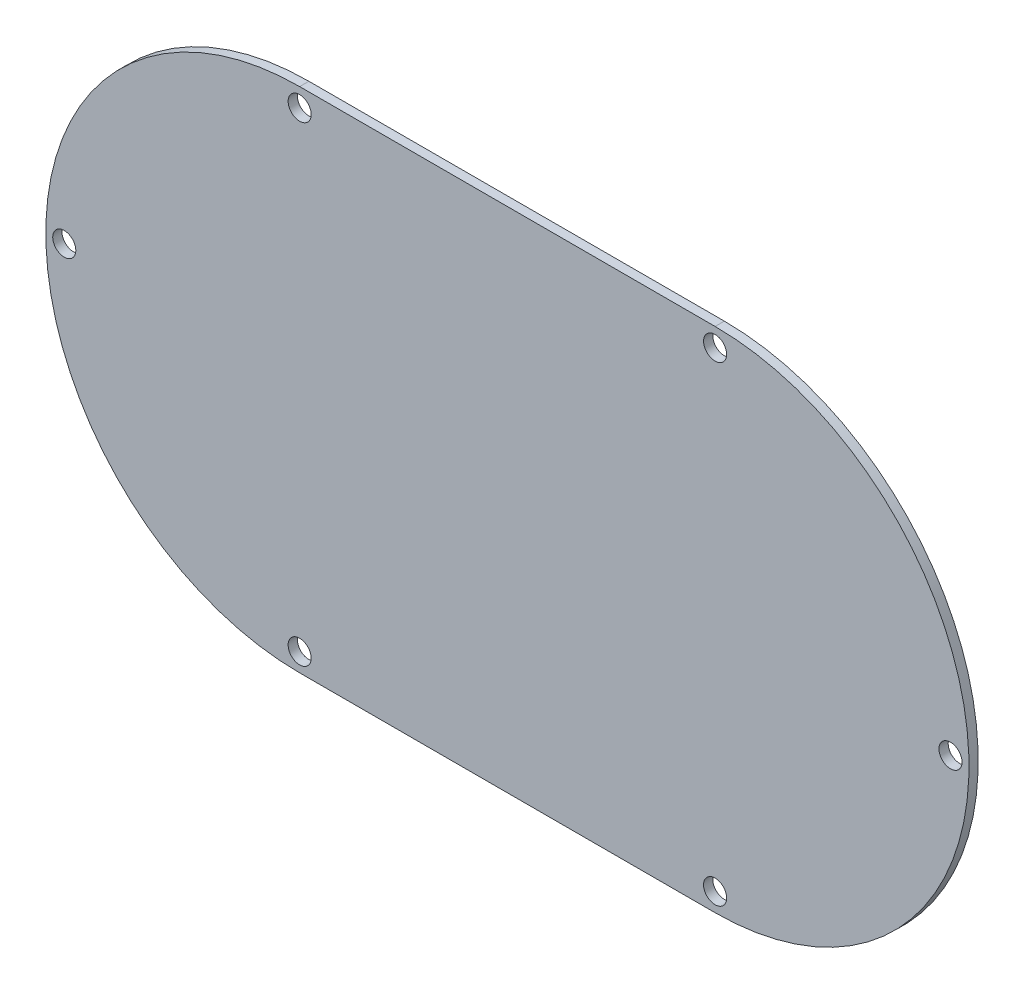
SolidWorks part; units mm, degrees
ref_plane "前视基准面" through (0, 0, 0) normal (0, 0, 1) x (1, 0, 0)
ref_plane "上视基准面" through (0, 0, 0) normal (0, 1, 0) x (1, 0, 0)
ref_plane "右视基准面" through (0, 0, 0) normal (1, 0, 0) x (0, 0, -1)
sketch "草图1" plane through (0, 0, 0) normal (0, 0, 1) x (1, 0, 0)
  line L0 (0, 55) -> (90, 55)
  line L1 (0, -55) -> (90, -55)
  arc A0 (0, 55) -> (0, -55) centre (0, 0) ccw
  arc A1 (90, -55) -> (90, 55) centre (90, 0) ccw
  dimension "D1" = 110
  dimension "D2" = 90
extrude "拉伸1" add sketch "草图1" along normal blind 2
sketch "草图2" plane through (0, 0, 0) normal (0, 0, -1) x (-1, 0, 0)
  circle A5 centre (-90, 51) radius 2.5
  circle A6 centre (0, 51) radius 2.5
  circle A11 centre (51, 0) radius 2.5
  circle A12 centre (0, -51) radius 2.5
  circle A13 centre (-90, -51) radius 2.5
  circle A14 centre (-141, 0) radius 2.5
  dimension "D2" = 5
  dimension "D3" = 5
extrude "切除-拉伸1" cut sketch "草图2" against normal blind 10
